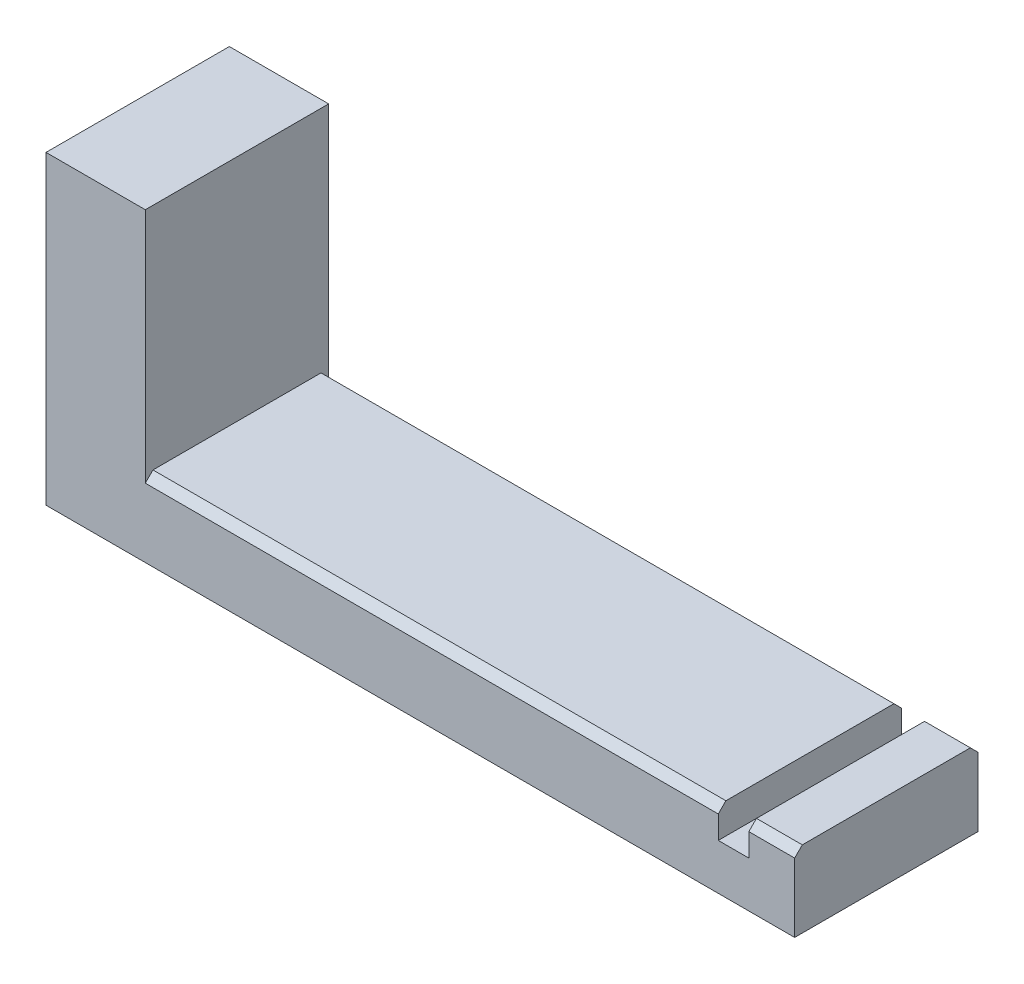
SolidWorks part; units mm, degrees
material "AISI 1020"
ref_plane "Front Plane" through (0, 0, 0) normal (0, 0, 1) x (1, 0, 0)
ref_plane "Top Plane" through (0, 0, 0) normal (0, 1, 0) x (1, 0, 0)
ref_plane "Right Plane" through (0, 0, 0) normal (1, 0, 0) x (0, 0, -1)
sketch "Sketch1" plane through (0, 0, 0) normal (0, 0, 1) x (1, 0, 0)
  line L0 (0, 0) -> (0, 40)
  line L1 (0, 40) -> (13, 40)
  line L2 (13, 40) -> (13, 10)
  line L3 (13, 10) -> (88, 10)
  line L4 (98, 10) -> (98, 0)
  line L5 (98, 0) -> (0, 0)
  line L6 (88, 10) -> (88, 6)
  line L7 (88, 6) -> (92, 6)
  line L8 (92, 6) -> (92, 10)
  line L9 (92, 10) -> (98, 10)
  dimension "D1" = 40
  dimension "D2" = 13
  dimension "D3" = 98
  dimension "D4" = 4
  dimension "D5" = 75
  dimension "D6" = 4
  dimension "D7" = 10
extrude "Boss-Extrude1" add sketch "Sketch1" along normal mid plane 24
chamfer "Chamfer1" distance 1 angle 45 4 edges at (95, 10, -12) (50.5, 10, -12) (95, 10, 12) (50.5, 10, 12)
